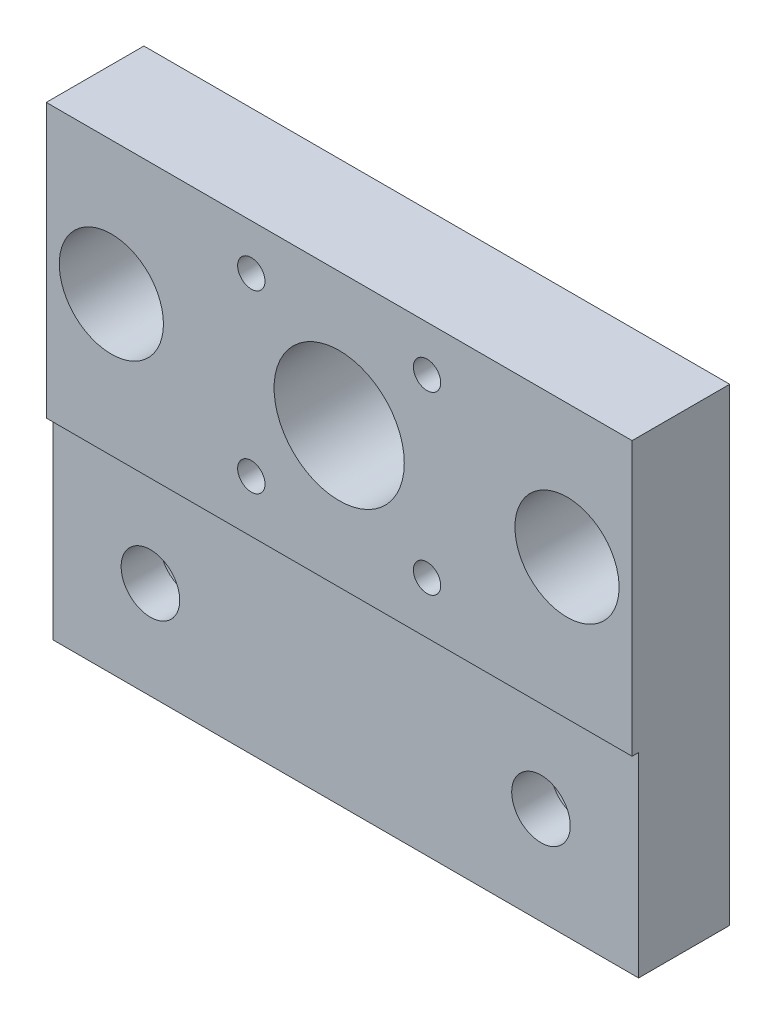
SolidWorks part; units mm, degrees
ref_plane "Front Plane" through (0, 0, 0) normal (0, 0, 1) x (1, 0, 0)
ref_plane "Top Plane" through (0, 0, 0) normal (0, 1, 0) x (1, 0, 0)
ref_plane "Right Plane" through (0, 0, 0) normal (1, 0, 0) x (0, 0, -1)
sketch "Sketch1" plane through (0, 0, 0) normal (0, 0, 1) x (1, 0, 0)
  line L1 (-45, -36) -> (45, -36)
  line L2 (-45, -36) -> (-45, 36)
  line L3 (-45, 36) -> (45, 36)
  line L4 (45, -36) -> (45, 36)
  line L5 (-45, -36) -> (45, 36) construction
  line L6 (-45, 36) -> (45, -36) construction
  point P0 (0, 0)
  dimension "D1" = 90
  dimension "D2" = 72
extrude "Boss-Extrude1" add sketch "Sketch1" along normal blind 15
sketch "Sketch2" plane through (0, 0, 15) normal (0, 0, 1) x (1, 0, 0)
  line L0 (45, -36) -> (45, 36) construction
  line L1 (-45, -36) -> (45, -36)
  line L2 (-45, -36) -> (-45, -6)
  line L3 (-45, -6) -> (45, -6)
  line L4 (45, -36) -> (45, -6)
  dimension "D1" = 30
extrude "Cut-Extrude1" cut sketch "Sketch2" against normal blind 1
sketch "Sketch3" plane through (0, 0, 15) normal (0, 0, 1) x (1, 0, 0)
  line L0 (45, 36) -> (-45, 36) construction
  line L1 (0, 0) -> (0, 36) construction
  line L2 (-14.5, 30) -> (0, 15.5) construction
  circle A0 centre (-14.5, 30) radius 5
  circle A2 centre (14.5, 30) radius 5
  circle A3 centre (14.5, 1) radius 5
  circle A4 centre (-14.5, 1) radius 5
  point P2 (-14.5, 35)
  point P18 (0, 15.5)
  dimension "D1" = 10
  dimension "D2" = 1
  dimension "D3" = 14.5
  dimension "D4" = 45
  dimension "D5" = 4
sketch "Sketch4" plane through (0, 0, 15) normal (0, 0, 1) x (1, 0, 0)
  line L0 (14.5, 30) -> (0, 15.5) construction
  line L1 (0, 15.5) -> (-14.5, 30) construction
  line L2 (0, 15.5) -> (0, 30.6749) construction
  circle A0 centre (0, 15.5) radius 10
  circle A1 centre (-35, 15.5) radius 8
  circle A2 centre (35, 15.5) radius 8
  dimension "D1" = 20
  dimension "D3" = 16
  dimension "D2" = 35
extrude "Cut-Extrude3" cut sketch "Sketch4" against normal through all
hole_wizard "CBORE for M8 SHCS1" positions "Sketch6" profile "Sketch8" counterbore size "M8" standard "ANSI Metric"
sketch "Sketch6" plane through (0, 0, 0) normal (0, 0, -1) x (-1, 0, 0)
  line L0 (45, -36) -> (30, -21) construction
  line L2 (45, -6) -> (45, -36) construction
  line L3 (0, -36) -> (0, 36) construction
  line L4 (45, -36) -> (-45, -36) construction
  line L5 (-45, 36) -> (45, 36) construction
  point P0 (30, -21)
  point P9 (-30, -21)
  dimension "D1" = 15
  dimension "D2" = 45
sketch "Sketch8" plane through (-30, -21, 0) normal (1, 0, 0) x (0, 1, 0)
  line L0 (0, 0) -> (0, 17.7039)
  line L1 (0, 17.7039) -> (4.5, 15)
  line L2 (4.5, 15) -> (4.5, 8)
  line L3 (4.5, 8) -> (7.5, 8)
  line L4 (7.5, 8) -> (7.5, 0)
  line L5 (7.5, 0) -> (0, 0)
  line L10 (0, 17.7039) -> (-4.5, 15) construction
  line L11 (0, -6.35) -> (0, 107.95) construction
  dimension "Hole Dia." = 9
  dimension "Hole Depth" = 15
  dimension "C'Bore Dia." = 15
  dimension "C'Bore Depth" = 8
  dimension "Drill Angle" = 118
hole_wizard "M5x0.8 Tapped Hole1" positions "Sketch9" profile "Sketch10" tap size "M5x0.8" standard "ANSI Metric" end condition up to next
sketch "Sketch9" plane through (0, 0, 0) normal (0, 0, -1) x (-1, 0, 0)
  line L0 (-13.5, 2) -> (13.5, 2) construction
  line L1 (13.5, 2) -> (13.5, 29) construction
  line L2 (13.5, 29) -> (-13.5, 29) construction
  line L3 (-13.5, 29) -> (-13.5, 2) construction
  line L5 (-13.5, 15.5) -> (0, 15.5) construction
  line L6 (0, 15.5) -> (0, 29) construction
  point P0 (13.5, 2)
  point P2 (13.5, 29)
  point P4 (-13.5, 29)
  point P6 (-13.5, 2)
  dimension "D1" = 27
sketch "Sketch10" plane through (-13.5, 2, 0) normal (1, 0, 0) x (0, 1, 0)
  line L0 (0, 0) -> (0, 15)
  line L1 (0, 15) -> (2.1, 15)
  line L2 (2.1, 15) -> (2.1, 0)
  line L5 (2.1, 0) -> (0, 0)
  line L11 (0, -6.35) -> (0, 107.95) construction
  dimension "Thru Tap Drill Dia." = 4.2
  dimension "Thru Tap Drill Depth" = 15
